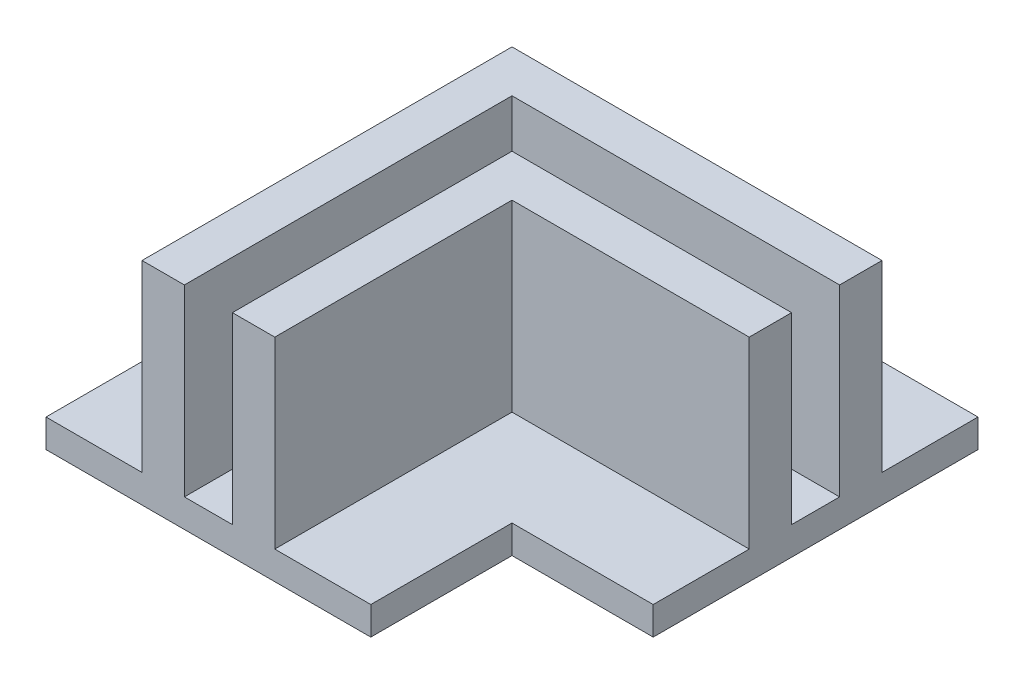
SolidWorks part; units mm, degrees
ref_plane "Plan de face" through (0, 0, 0) normal (0, 0, 1) x (1, 0, 0)
ref_plane "Plan de dessus" through (0, 0, 0) normal (0, 1, 0) x (1, 0, 0)
ref_plane "Plan de droite" through (0, 0, 0) normal (1, 0, 0) x (0, 0, -1)
sketch "Esquisse1" plane through (0, 0, 0) normal (0, 1, 0) x (1, 0, 0)
  line L0 (-8.3929, 11.1607) -> (4.6071, 11.1607)
  line L1 (-8.3929, 11.1607) -> (-8.3929, -8.8393)
  line L2 (4.6071, 11.1607) -> (4.6071, -8.8393)
  line L3 (4.6071, -8.8393) -> (-8.3929, -8.8393)
  dimension "D1" = 13
  dimension "D2" = 20
extrude "Boss.-Extru.1" add sketch "Esquisse1" along normal blind 15
sketch "Esquisse2" plane through (0, 15, 0) normal (0, 1, 0) x (1, 0, 0)
  line L0 (4.6071, 11.1607) -> (-8.3929, 11.1607) construction
  line L2 (-3.3929, 11.1607) -> (-0.3929, 11.1607)
  line L6 (-8.3929, -8.8393) -> (4.6071, -8.8393) construction
  line L7 (-3.3929, 11.1607) -> (-0.3929, 11.1607)
  line L8 (-3.3929, 11.1607) -> (-3.3929, -8.8393)
  line L9 (-3.3929, -8.8393) -> (-0.3929, -8.8393)
  line L10 (-0.3929, 11.1607) -> (-0.3929, -8.8393)
  line L12 (-8.3929, 11.1607) -> (-6.3929, 11.1607)
  line L13 (-8.3929, 11.1607) -> (-8.3929, -8.8393)
  line L14 (-8.3929, -8.8393) -> (-6.3929, -8.8393)
  line L15 (-6.3929, 11.1607) -> (-6.3929, -8.8393)
  line L16 (2.6071, 11.1607) -> (4.6071, 11.1607)
  line L17 (2.6071, 11.1607) -> (2.6071, -8.8393)
  line L18 (2.6071, -8.8393) -> (4.6071, -8.8393)
  line L19 (4.6071, 11.1607) -> (4.6071, -8.8393)
  point P0 (-3.3929, 11.1607)
  point P1 (-0.3929, 11.1607)
  point P7 (-6.3929, 11.1607)
  point P8 (2.6071, 11.1607)
  line M5 (-8.3929, 11.1607) -> (-8.3929, -8.8393)
  line M6 (-8.3929, -8.8393) -> (4.6071, -8.8393)
  line M7 (4.6071, -8.8393) -> (4.6071, 11.1607)
  line M8 (4.6071, 11.1607) -> (-8.3929, 11.1607)
  dimension "D1" = 5
  dimension "D2" = 5
  dimension "D3" = 3
  dimension "D4" = 3
extrude "Enlèv. mat.-Extru.2" cut sketch "Esquisse2" against normal blind 13 contours L15 M8 M5 M6 | L10 L8 M8 M6 | L17 M8 M6 M7
sketch "Esquisse4" plane through (-8.3929, 0, 0) normal (-1, 0, 0) x (0, 0, 1)
  line L4 (8.8393, 2) -> (-11.1607, 2)
  line L5 (-11.1607, 2) -> (-11.1607, 0)
  line L6 (-11.1607, 0) -> (8.8393, 0)
  line L7 (8.8393, 0) -> (8.8393, 2)
  line L8 (8.8393, 2) -> (-11.1607, 2)
  line L9 (-11.1607, 2) -> (-11.1607, 0)
  line L10 (-11.1607, 0) -> (8.8393, 0)
  line L11 (8.8393, 0) -> (8.8393, 2)
  dimension "D1" = 0
extrude "Boss.-Extru.2" add sketch "Esquisse4" along normal blind 5
sketch "Esquisse5" plane through (4.6071, 0, 0) normal (1, 0, 0) x (0, 0, -1)
  line L4 (11.1607, 2) -> (-8.8393, 2)
  line L5 (-8.8393, 2) -> (-8.8393, 0)
  line L6 (-8.8393, 0) -> (11.1607, 0)
  line L7 (11.1607, 0) -> (11.1607, 2)
  line L8 (11.1607, 2) -> (-8.8393, 2)
  line L9 (-8.8393, 2) -> (-8.8393, 0)
  line L10 (-8.8393, 0) -> (11.1607, 0)
  line L11 (11.1607, 0) -> (11.1607, 2)
  dimension "D1" = 0
extrude "Boss.-Extru.3" add sketch "Esquisse5" along normal blind 5
sketch "Esquisse6" plane through (-0.3929, 0, 0) normal (-1, 0, 0) x (0, 0, 1)
  line L4 (8.8393, 15) -> (-11.1607, 15)
  line L5 (-11.1607, 15) -> (-11.1607, 2)
  line L6 (-11.1607, 2) -> (8.8393, 2)
  line L7 (8.8393, 2) -> (8.8393, 15)
  line L8 (8.8393, 15) -> (-11.1607, 15)
  line L9 (-11.1607, 15) -> (-11.1607, 2)
  line L10 (-11.1607, 2) -> (8.8393, 2)
  line L11 (8.8393, 2) -> (8.8393, 15)
  dimension "D1" = 0
extrude "Enlèv. mat.-Extru.3" cut sketch "Esquisse6" against normal blind 0.2
sketch "Esquisse7" plane through (-3.3929, 0, 0) normal (1, 0, 0) x (0, 0, -1)
  line L4 (11.1607, 15) -> (-8.8393, 15)
  line L5 (-8.8393, 15) -> (-8.8393, 2)
  line L6 (-8.8393, 2) -> (11.1607, 2)
  line L7 (11.1607, 2) -> (11.1607, 15)
  line L8 (11.1607, 15) -> (-8.8393, 15)
  line L9 (-8.8393, 15) -> (-8.8393, 2)
  line L10 (-8.8393, 2) -> (11.1607, 2)
  line L11 (11.1607, 2) -> (11.1607, 15)
  dimension "D1" = 0
extrude "Enlèv. mat.-Extru.4" cut sketch "Esquisse7" against normal blind 0.2
sketch "Esquisse8" plane through (2.6071, 0, 0) normal (1, 0, 0) x (0, 0, -1)
  line L4 (11.1607, 15) -> (-8.8393, 15)
  line L5 (-8.8393, 15) -> (-8.8393, 2)
  line L6 (-8.8393, 2) -> (11.1607, 2)
  line L7 (11.1607, 2) -> (11.1607, 15)
  line L8 (11.1607, 15) -> (-8.8393, 15)
  line L9 (-8.8393, 15) -> (-8.8393, 2)
  line L10 (-8.8393, 2) -> (11.1607, 2)
  line L11 (11.1607, 2) -> (11.1607, 15)
  dimension "D1" = 0
extrude "Boss.-Extru.4" add sketch "Esquisse8" along normal blind 0.2
sketch "Esquisse9" plane through (-6.3929, 0, 0) normal (-1, 0, 0) x (0, 0, 1)
  line L4 (8.8393, 15) -> (-11.1607, 15)
  line L5 (-11.1607, 15) -> (-11.1607, 2)
  line L6 (-11.1607, 2) -> (8.8393, 2)
  line L7 (8.8393, 2) -> (8.8393, 15)
  line L8 (8.8393, 15) -> (-11.1607, 15)
  line L9 (-11.1607, 15) -> (-11.1607, 2)
  line L10 (-11.1607, 2) -> (8.8393, 2)
  line L11 (8.8393, 2) -> (8.8393, 15)
  dimension "D1" = 0
extrude "Boss.-Extru.5" add sketch "Esquisse9" along normal blind 0.2
sketch "Esquisse11" plane through (0, 0, -11.1607) normal (0, 0, -1) x (-1, 0, 0)
  line L12 (6.5929, 2) -> (6.5929, 15)
  line L13 (6.5929, 15) -> (3.5929, 15)
  line L14 (3.5929, 15) -> (3.5929, 2)
  line L15 (3.5929, 2) -> (0.1929, 2)
  line L16 (0.1929, 2) -> (0.1929, 15)
  line L17 (0.1929, 15) -> (-2.8071, 15)
  line L18 (-2.8071, 15) -> (-2.8071, 2)
  line L19 (-2.8071, 2) -> (-9.6071, 2)
  line L20 (-9.6071, 2) -> (-9.6071, 0)
  line L21 (-9.6071, 0) -> (13.3929, 0)
  line L22 (13.3929, 0) -> (13.3929, 2)
  line L23 (13.3929, 2) -> (6.5929, 2)
  line L24 (6.5929, 2) -> (6.5929, 15)
  line L25 (6.5929, 15) -> (3.5929, 15)
  line L26 (3.5929, 15) -> (3.5929, 2)
  line L27 (3.5929, 2) -> (0.1929, 2)
  line L28 (0.1929, 2) -> (0.1929, 15)
  line L29 (0.1929, 15) -> (-2.8071, 15)
  line L30 (-2.8071, 15) -> (-2.8071, 2)
  line L31 (-2.8071, 2) -> (-9.6071, 2)
  line L32 (-9.6071, 2) -> (-9.6071, 0)
  line L33 (-9.6071, 0) -> (13.3929, 0)
  line L34 (13.3929, 0) -> (13.3929, 2)
  line L35 (13.3929, 2) -> (6.5929, 2)
  dimension "D1" = 0
extrude "Enlèv. mat.-Extru.5" cut sketch "Esquisse11" against normal blind 10
sketch "Esquisse12" plane through (0, 0, 0) normal (0, 1, 0) x (1, 0, 0)
  line L0 (9.6071, 1.1607) -> (19.6071, 1.1607)
  line L1 (19.6071, 1.1607) -> (19.6071, 24.1607)
  line L2 (9.6071, 1.1607) -> (-13.3929, 1.1607)
  line L3 (-13.3929, 1.1607) -> (-13.3929, 24.1607)
  line L4 (-13.3929, 24.1607) -> (19.6071, 24.1607)
  dimension "D1" = 10
  dimension "D2" = 23
extrude "Boss.-Extru.6" add sketch "Esquisse12" along normal up to vertex
sketch "Esquisse13" plane through (0, 2, 0) normal (0, 1, 0) x (1, 0, 0)
  line L0 (2.8071, 1.1607) -> (-0.1929, 1.1607)
  line L1 (-0.1929, 1.1607) -> (-0.1929, 24.1607)
  line L2 (19.6071, 24.1607) -> (-13.3929, 24.1607) construction
  line L3 (-0.1929, 24.1607) -> (2.8071, 24.1607)
  line L4 (2.8071, 24.1607) -> (2.8071, 1.7899)
  line L5 (2.8071, 1.7899) -> (2.8071, 1.1607)
  line L6 (-3.5929, 1.1607) -> (-6.5929, 1.1607)
  line L7 (-6.5929, 1.1607) -> (-6.5929, 24.1607)
  line L8 (-6.5929, 24.1607) -> (-3.5929, 24.1607)
  line L9 (-3.5929, 24.1607) -> (-3.5929, 1.1607)
extrude "Boss.-Extru.7" add sketch "Esquisse13" along normal up to vertex (13 mm away)
sketch "Esquisse14" plane through (0, 2, 0) normal (0, 1, 0) x (1, 0, 0)
  line L0 (19.6071, 1.1607) -> (19.6071, 24.1607) construction
  line L1 (-13.3929, -8.8393) -> (-13.3929, 24.1607) construction
  line L2 (19.6071, 7.9607) -> (-13.3929, 7.9607)
  line L3 (19.6071, 7.9607) -> (19.6071, 10.9607)
  line L4 (19.6071, 10.9607) -> (-13.3929, 10.9607)
  line L5 (-13.3929, 7.9607) -> (-13.3929, 10.9607)
  line L8 (19.6071, 17.3607) -> (19.6071, 20.5054)
  line L10 (-13.3929, 17.3607) -> (-13.3929, 20.5054)
  line L11 (19.6071, 17.3607) -> (-13.3929, 17.3607)
  line L12 (19.6071, 17.3607) -> (19.6071, 14.3607)
  line L13 (19.6071, 14.3607) -> (-13.3929, 14.3607)
  line L14 (-13.3929, 17.3607) -> (-13.3929, 14.3607)
  point P0 (19.6071, 7.9607)
  point P1 (19.6071, 17.3607)
  line M8 (2.8071, 24.1607) -> (2.8071, -8.8393)
  line M12 (19.6071, 1.1607) -> (19.6071, 24.1607)
  dimension "D1" = 6.8
  dimension "D2" = 6.8
  dimension "D3" = 3
  dimension "D4" = 3.1447
  dimension "D5" = 3
extrude "Boss.-Extru.8" add sketch "Esquisse14" along normal up to vertex (13 mm away) contours L4 L2 M12 M8 | L13 L11 M12 M8 | L5 L2 L4 M8 | L11 L14 L13 M8
sketch "Esquisse18" plane through (0, 0, -10.9607) normal (0, 0, -1) x (-1, 0, 0)
  line L4 (0.1929, 15) -> (0.1929, 2)
  line L5 (0.1929, 2) -> (3.5929, 2)
  line L6 (3.5929, 2) -> (3.5929, 15)
  line L7 (3.5929, 15) -> (0.1929, 15)
  line L8 (0.1929, 15) -> (0.1929, 2)
  line L9 (0.1929, 2) -> (3.5929, 2)
  line L10 (3.5929, 2) -> (3.5929, 15)
  line L11 (3.5929, 15) -> (0.1929, 15)
  dimension "D1" = 0
extrude "Enlèv. mat.-Extru.8" cut sketch "Esquisse18" against normal blind 10
sketch "Esquisse19" plane through (0, 0, -17.3607) normal (0, 0, -1) x (-1, 0, 0)
  line L4 (6.5929, 15) -> (6.5929, 2)
  line L5 (6.5929, 2) -> (13.3929, 2)
  line L6 (13.3929, 2) -> (13.3929, 15)
  line L7 (13.3929, 15) -> (6.5929, 15)
  line L8 (6.5929, 15) -> (6.5929, 2)
  line L9 (6.5929, 2) -> (13.3929, 2)
  line L10 (13.3929, 2) -> (13.3929, 15)
  line L11 (13.3929, 15) -> (6.5929, 15)
  dimension "D1" = 0
extrude "Enlèv. mat.-Extru.9" cut sketch "Esquisse19" against normal blind 10
sketch "Esquisse20" plane through (2.8071, 0, 0) normal (1, 0, 0) x (0, 0, -1)
  line L4 (24.1607, 15) -> (17.3607, 15)
  line L5 (17.3607, 15) -> (17.3607, 2)
  line L6 (17.3607, 2) -> (24.1607, 2)
  line L7 (24.1607, 2) -> (24.1607, 15)
  line L8 (24.1607, 15) -> (17.3607, 15)
  line L9 (17.3607, 15) -> (17.3607, 2)
  line L10 (17.3607, 2) -> (24.1607, 2)
  line L11 (24.1607, 2) -> (24.1607, 15)
  dimension "D1" = 0
extrude "Enlèv. mat.-Extru.10" cut sketch "Esquisse20" against normal blind 10
sketch "Esquisse21" plane through (2.8071, 0, 0) normal (1, 0, 0) x (0, 0, -1)
  line L4 (14.3607, 2) -> (14.3607, 15)
  line L5 (14.3607, 15) -> (10.9607, 15)
  line L6 (10.9607, 15) -> (10.9607, 2)
  line L7 (10.9607, 2) -> (14.3607, 2)
  line L8 (14.3607, 2) -> (14.3607, 15)
  line L9 (14.3607, 15) -> (10.9607, 15)
  line L10 (10.9607, 15) -> (10.9607, 2)
  line L11 (10.9607, 2) -> (14.3607, 2)
  dimension "D1" = 0
extrude "Enlèv. mat.-Extru.11" cut sketch "Esquisse21" against normal blind 5
